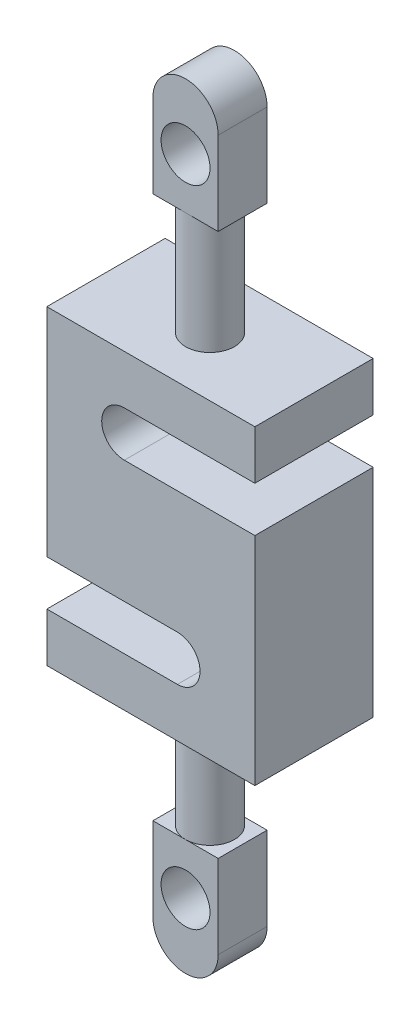
SolidWorks part; units mm, degrees
ref_plane "Front Plane" through (0, 0, 0) normal (0, 0, 1) x (1, 0, 0)
ref_plane "Top Plane" through (0, 0, 0) normal (0, 1, 0) x (1, 0, 0)
ref_plane "Right Plane" through (0, 0, 0) normal (1, 0, 0) x (0, 0, -1)
sketch "Sketch1" plane through (0, 0, 0) normal (0, 0, 1) x (1, 0, 0)
  line L1 (-51, -30) -> (-19, -30)
  line L3 (-19, -41.1) -> (-51, -41.1)
  line L4 (-51, -41.1) -> (-51, -53.1)
  line L5 (-51, -53.1) -> (0, -53.1)
  line L6 (0, -53.1) -> (0, 0)
  line L7 (0, 0) -> (-32, 0)
  line L11 (-51, 23.1) -> (0, 23.1)
  line L12 (0, 23.1) -> (0, 11.1)
  line L13 (0, 11.1) -> (-32, 11.1)
  line L14 (-51, 23.1) -> (-51, -30)
  arc A0 (-32, 11.1) -> (-32, 0) centre (-32, 5.55) ccw
  arc A1 (-19, -30) -> (-19, -41.1) centre (-19, -35.55) cw
  point P15 (-17.0428, -41.1)
  dimension "D4" = 32
  dimension "D1" = 51
  dimension "D2" = 76.2
  dimension "D3" = 30
  dimension "D6" = 12
extrude "Boss-Extrude1" add sketch "Sketch1" along normal blind 29
sketch "Sketch2" plane through (-51, 0, 0) normal (-1, 0, 0) x (0, 0, 1)
  line L0 (14.5, 23.1) -> (14.5, -30) construction
  line L1 (29, 23.1) -> (0, 23.1) construction
  line L2 (29, -30) -> (0, -30) construction
  line L3 (0, -15) -> (29, -15) construction
  line L4 (0, 23.1) -> (0, -30) construction
  line L5 (29, 23.1) -> (29, -30) construction
  circle A1 centre (14.5, -15) radius 5
  dimension "D2" = 10
  dimension "D1" = 15
sketch "Sketch3" plane through (0, 23.1, 0) normal (0, 1, 0) x (1, 0, 0)
  line L0 (-25.5, 0) -> (-25.5, -29) construction
  line L1 (0, 0) -> (-51, 0) construction
  line L2 (0, -29) -> (-51, -29) construction
  line L3 (-51, -14.5) -> (0, -14.5) construction
  line L4 (-51, -29) -> (-51, 0) construction
  line L5 (0, -29) -> (0, 0) construction
  point P12 (-25.5, -14.5)
  point P13 (0, 0)
  point P14 (0, 0)
ref_plane "Plane2" through (0, -15, 0) normal (0, 1, 0) x (1, 0, 0)
sketch "Sketch14" plane through (0, 23.1, 0) normal (0, 1, 0) x (1, 0, 0)
  line L0 (-25.5, 0) -> (-25.5, -29) construction
  circle A0 centre (-25.5, -14.5) radius 6
  dimension "D1" = 12
extrude "Boss-Extrude3" add sketch "Sketch14" along normal blind 28.45
sketch "Sketch15" plane through (0, 51.55, 0) normal (0, 1, 0) x (1, 0, 0)
  line L1 (-33.5, -20.5) -> (-17.5, -20.5)
  line L2 (-33.5, -20.5) -> (-33.5, -8.5)
  line L3 (-33.5, -8.5) -> (-17.5, -8.5)
  line L4 (-17.5, -20.5) -> (-17.5, -8.5)
  line L5 (-33.5, -20.5) -> (-17.5, -8.5) construction
  line L6 (-33.5, -8.5) -> (-17.5, -20.5) construction
  point P0 (-25.5, -14.5)
  dimension "D1" = 16
  dimension "D2" = 12
extrude "Boss-Extrude4" add sketch "Sketch15" along normal blind 20.45
sketch "Sketch16" plane through (0, 0, 20.5) normal (0, 0, 1) x (1, 0, 0)
  line L2 (-33.5, 72) -> (-33.5, 51.55) construction
  line L8 (-33.5, 51.55) -> (-25.5, 51.55)
  line L9 (-25.5, 51.55) -> (-17.5, 51.55)
  line L10 (-17.5, 51.55) -> (-17.5, 72)
  line L11 (-17.5, 72) -> (-33.5, 72)
  line L12 (-33.5, 72) -> (-33.5, 51.55)
  line L16 (-17.5, 72) -> (-33.5, 72)
  arc A0 (-33.5, 72) -> (-17.5, 72) centre (-25.5, 72) cw
  dimension "D1" = 0
extrude "Boss-Extrude5" add sketch "Sketch16" against normal up to vertex
sketch "Sketch17" plane through (0, 0, 20.5) normal (0, 0, 1) x (1, 0, 0)
  line L0 (-51, 23.1) -> (0, 23.1) construction
  line L1 (-25.5, 80) -> (-25.5, 51.55) construction
  circle A0 centre (-25.5, 64) radius 6
  arc A1 (-17.5, 72) -> (-33.5, 72) centre (-25.5, 72) ccw construction
  point P2 (0, 0)
  dimension "D1" = 40.9
  dimension "D2" = 12
extrude "Cut-Extrude1" cut sketch "Sketch17" against normal through all
mirror "Mirror7" about plane through (0, -15, 0) normal (0, 1, 0) of "Boss-Extrude5", "Cut-Extrude1", "Boss-Extrude3", "Boss-Extrude4"
